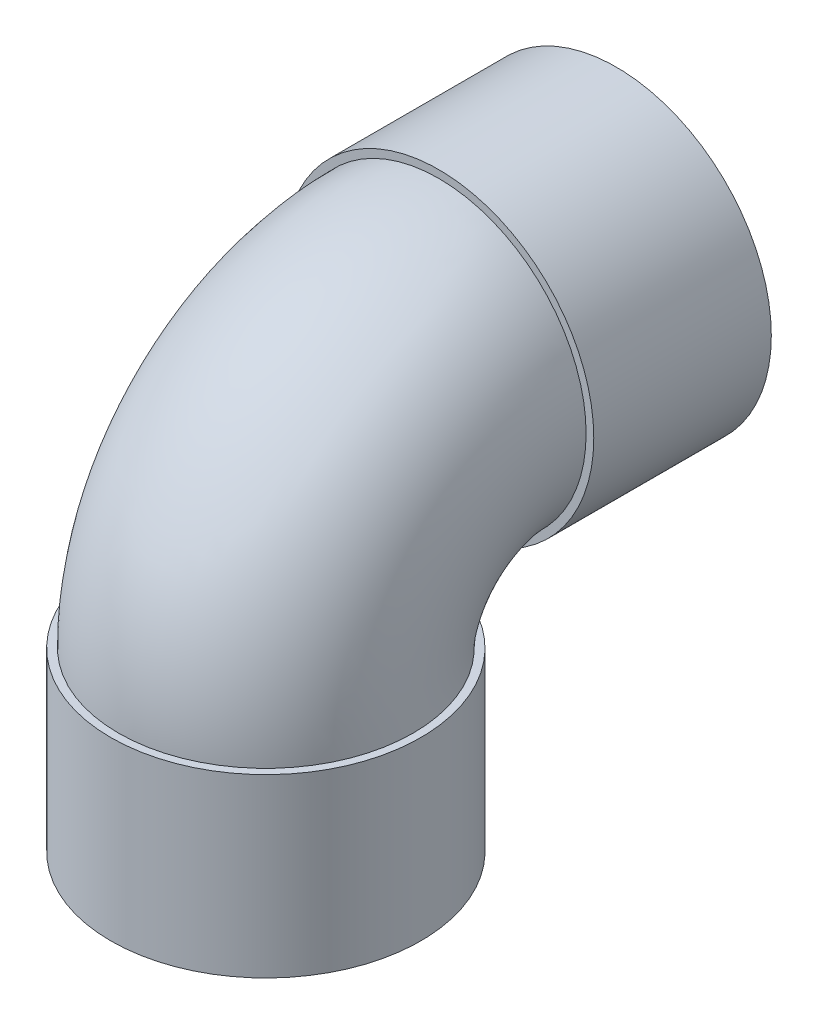
SolidWorks part; units mm, degrees
ref_plane "Plan de face" through (0, 0, 0) normal (0, 0, 1) x (1, 0, 0)
ref_plane "Plan de dessus" through (0, 0, 0) normal (0, 1, 0) x (1, 0, 0)
ref_plane "Plan de droite" through (0, 0, 0) normal (1, 0, 0) x (0, 0, -1)
sketch "Esquisse1" plane through (0, 0, 0) normal (0, 0, 1) x (1, 0, 0)
  line L0 (0, -30.6831) -> (89.1646, -30.6831)
  circle A0 centre (0, 0) radius 26.14
revolve "Révol.-Mince1" add sketch "Esquisse1" angle 90 about L0
sketch "Esquisse2" plane through (0, 0, 0) normal (0, 0, -1) x (-1, 0, 0)
  circle A0 centre (0, 0) radius 27.5
extrude "Extru.-Mince1" add sketch "Esquisse2" along normal blind 31.5 thin thin type one direction reverse wall 2.25
sketch "Esquisse3" plane through (0, -30.6831, 0) normal (0, -1, 0) x (1, 0, 0)
  circle A0 centre (0, 30.6831) radius 27.5
extrude "Extru.-Mince2" add sketch "Esquisse3" along normal blind 31.25 thin thin type one direction reverse wall 2.25
